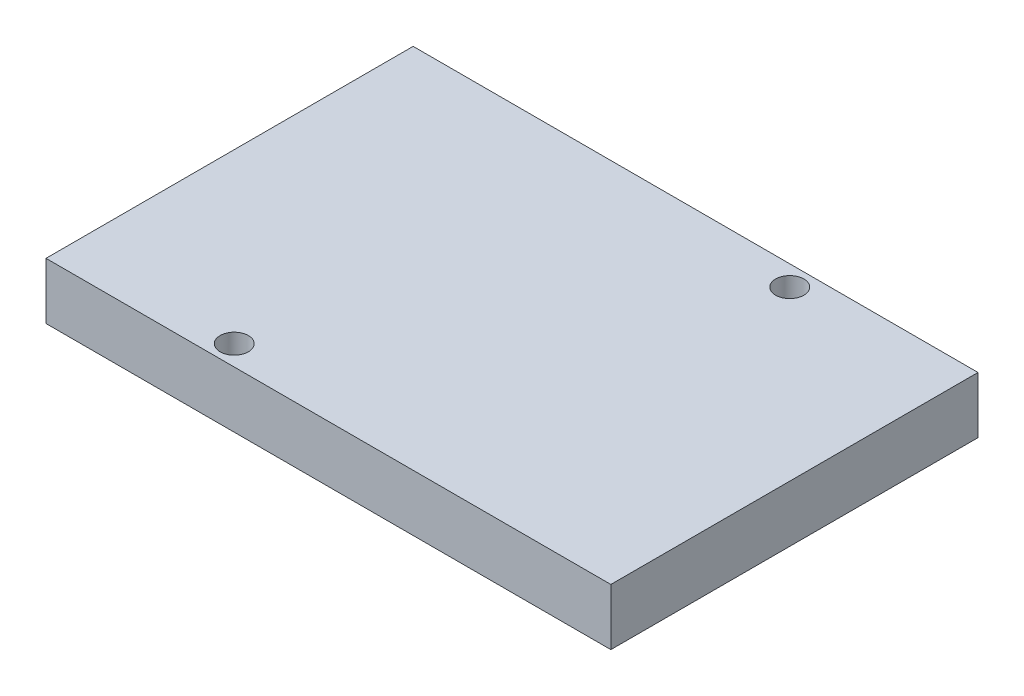
SolidWorks part; units mm, degrees
ref_plane "Front Plane" through (0, 0, 0) normal (0, 0, 1) x (1, 0, 0)
ref_plane "Top Plane" through (0, 0, 0) normal (0, 1, 0) x (1, 0, 0)
ref_plane "Right Plane" through (0, 0, 0) normal (1, 0, 0) x (0, 0, -1)
sketch "Sketch1" plane through (0, 0, 0) normal (0, 1, 0) x (1, 0, 0)
  line L1 (0, 0) -> (100, 0)
  line L2 (0, 0) -> (0, 65)
  line L3 (0, 65) -> (100, 65)
  line L4 (100, 0) -> (100, 65)
  dimension "D1" = 100
  dimension "D2" = 65
extrude "Boss-Extrude1" add sketch "Sketch1" along normal blind 10
sketch "Sketch2" plane through (0, 0, -65) normal (0, 0, -1) x (-1, 0, 0)
  line L0 (0, 10) -> (0, 0) construction
  line L1 (-100, 10) -> (0, 10) construction
  circle A0 centre (-59, 5) radius 2.5
  circle A1 centre (-41, 5) radius 2.5
  point P6 (-55.222, 4.6016)
  dimension "D1" = 5
  dimension "D2" = 5
  dimension "D3" = 18
  dimension "D4" = 41
  dimension "D5" = 5
  dimension "D6" = 5
extrude "Cut-Extrude1" cut sketch "Sketch2" against normal blind 10
sketch "Sketch3" plane through (0, 10, 0) normal (0, 1, 0) x (1, 0, 0)
  line L0 (0, 0) -> (100, 0) construction
  line L1 (0, 65) -> (0, 0) construction
  circle A0 centre (29.75, 3.575) radius 2.5
  circle A1 centre (70.25, 61.425) radius 2.5
  dimension "D1" = 5
  dimension "D2" = 5
  dimension "D3" = 40.5
  dimension "D4" = 57.85
  dimension "D5" = 3.575
  dimension "D6" = 29.75
extrude "Cut-Extrude2" cut sketch "Sketch3" along direction (0, -1, 0) on the side against the normal offset from surface (4 mm away) 4 contours A1 | A0
